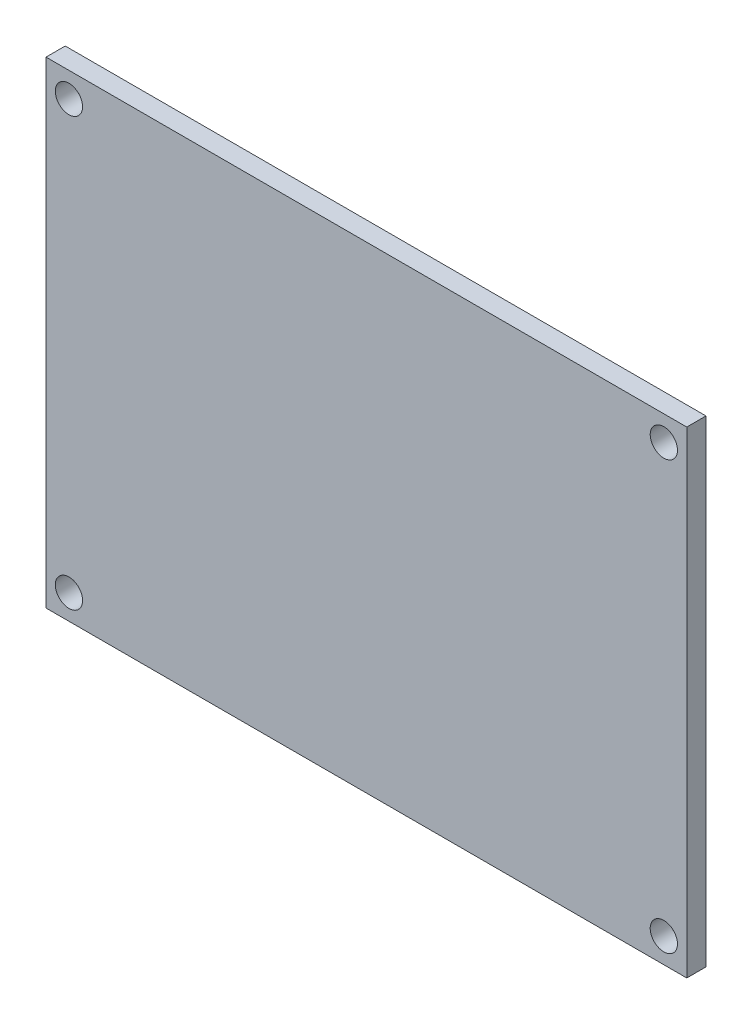
SolidWorks part; units mm, degrees
material "E-Glass Fiber"
ref_plane "Front Plane" through (0, 0, 0) normal (0, 0, 1) x (1, 0, 0)
ref_plane "Top Plane" through (0, 0, 0) normal (0, 1, 0) x (1, 0, 0)
ref_plane "Right Plane" through (0, 0, 0) normal (1, 0, 0) x (0, 0, -1)
sketch "Sketch1" plane through (0, 0, 0) normal (0, 0, 1) x (1, 0, 0)
  line L1 (-25.85, 19.25) -> (25.85, 19.25)
  line L2 (-25.85, 19.25) -> (-25.85, -19.25)
  line L3 (-25.85, -19.25) -> (25.85, -19.25)
  line L4 (25.85, 19.25) -> (25.85, -19.25)
  line L5 (-25.85, 19.25) -> (25.85, -19.25) construction
  line L6 (-25.85, -19.25) -> (25.85, 19.25) construction
  point P0 (0, 0)
  dimension "D1" = 51.7
  dimension "D2" = 38.5
extrude "Boss-Extrude1" add sketch "Sketch1" along normal blind 1.55
sketch "Sketch2" plane through (0, 0, 1.55) normal (0, 0, 1) x (1, 0, 0)
  line L5 (-24, 17.25) -> (24, 17.25) construction
  line L6 (-24, 17.25) -> (-24, -17.25) construction
  line L7 (-24, -17.25) -> (24, -17.25) construction
  line L8 (24, 17.25) -> (24, -17.25) construction
  line L9 (-24, 17.25) -> (24, -17.25) construction
  line L10 (-24, -17.25) -> (24, 17.25) construction
  circle A5 centre (-24, 17.25) radius 1.1
  circle A6 centre (24, 17.25) radius 1.1
  circle A7 centre (24, -17.25) radius 1.1
  circle A8 centre (-24, -17.25) radius 1.1
  point P0 (0, 0)
  dimension "D1" = 48
  dimension "D3" = 2.2
  dimension "D2" = 34.5
extrude "Cut-Extrude1" cut sketch "Sketch2" against normal up to next
